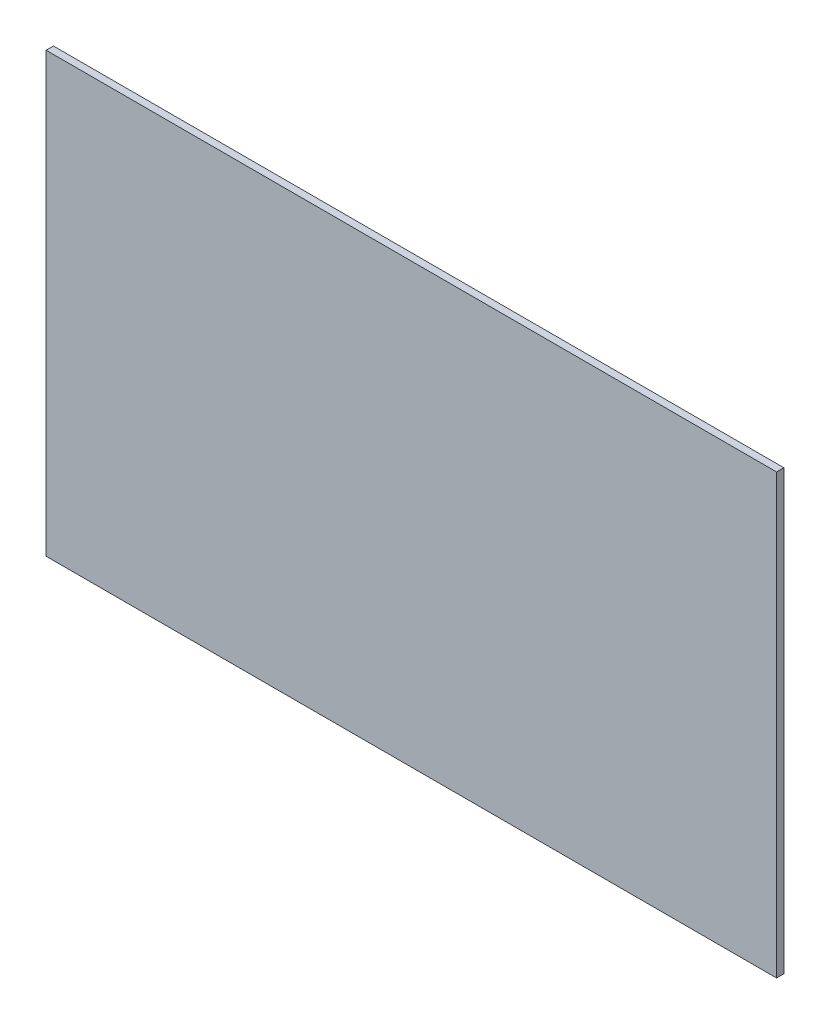
SolidWorks part; units mm, degrees
material "Verre"
ref_plane "Plan de face" through (0, 0, 0) normal (0, 0, 1) x (1, 0, 0)
ref_plane "Plan de dessus" through (0, 0, 0) normal (0, 1, 0) x (1, 0, 0)
ref_plane "Plan de droite" through (0, 0, 0) normal (1, 0, 0) x (0, 0, -1)
sketch "Esquisse1" plane through (0, 0, 0) normal (0, 0, 1) x (1, 0, 0)
  line L1 (250, -150) -> (-250, -150)
  line L2 (250, -150) -> (250, 150)
  line L3 (250, 150) -> (-250, 150)
  line L4 (-250, -150) -> (-250, 150)
  line L5 (250, -150) -> (-250, 150) construction
  line L6 (250, 150) -> (-250, -150) construction
  point P0 (0, 0)
  dimension "D1" = 300
  dimension "D2" = 500
extrude "Boss.-Extru.1" add sketch "Esquisse1" along normal blind 5
